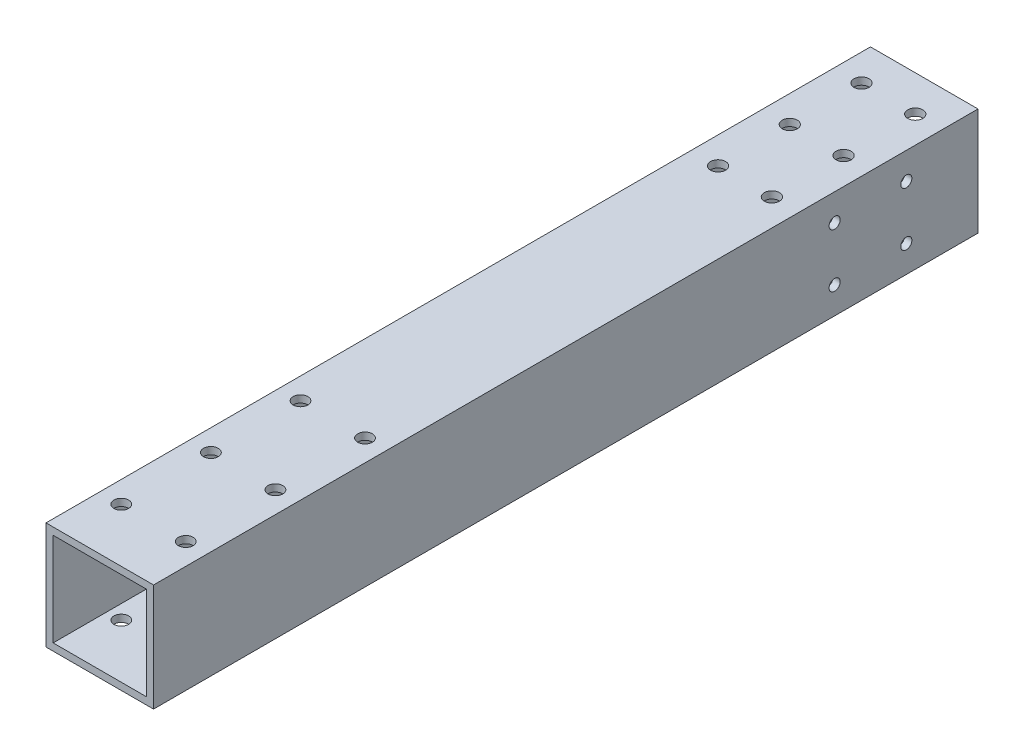
SolidWorks part; units mm, degrees
material "6063-T1"
ref_plane "前视基准面" through (0, 0, 0) normal (0, 0, 1) x (1, 0, 0)
ref_plane "上视基准面" through (0, 0, 0) normal (0, 1, 0) x (1, 0, 0)
ref_plane "右视基准面" through (0, 0, 0) normal (1, 0, 0) x (0, 0, -1)
other "Configuration Table"
sketch "草图1" plane through (0, 0, 0) normal (0, 0, 1) x (1, 0, 0)
  line L1 (-15, 15) -> (15, 15)
  line L2 (-15, 15) -> (-15, -15)
  line L3 (-15, -15) -> (15, -15)
  line L4 (15, 15) -> (15, -15)
  line L5 (-15, 15) -> (15, -15) construction
  line L6 (-15, -15) -> (15, 15) construction
  line L7 (-13, 13) -> (13, 13)
  line L8 (-13, 13) -> (-13, -13)
  line L9 (-13, -13) -> (13, -13)
  line L10 (13, 13) -> (13, -13)
  line L11 (-13, 13) -> (13, -13) construction
  line L12 (-13, -13) -> (13, 13) construction
  point P0 (0, 0)
  point P6 (0, 0)
  dimension "D1" = 30
  dimension "D2" = 2
extrude "凸台-拉伸1" add sketch "草图1" along normal blind 230
sketch "草图2" plane through (0, -15, 0) normal (0, -1, 0) x (1, 0, 0)
  line L0 (-15, 0) -> (15, 0) construction
  line L1 (0, 0) -> (0, 12.9561) construction
  line L2 (0, 230) -> (0, 248.9247) construction
  line L3 (-15, 230) -> (15, 230) construction
  line L4 (-15, 230) -> (-15, 0) construction
  line L5 (15, 230) -> (15, 0) construction
  circle A1 centre (-7.5, 10) radius 2.1
  circle A2 centre (7.5, 10) radius 2.1
  circle A3 centre (7.5, 30) radius 2.1
  circle A4 centre (7.5, 50) radius 2.1
  circle A5 centre (-7.5, 30) radius 2.1
  circle A6 centre (-7.5, 50) radius 2.1
  circle A7 centre (-9, 215) radius 2.05
  circle A8 centre (9, 215) radius 2.05
  circle A9 centre (9, 190) radius 2.05
  circle A10 centre (9, 165) radius 2.05
  circle A11 centre (-9, 190) radius 2.05
  circle A12 centre (-9, 165) radius 2.05
  dimension "D2" = 4.2
  dimension "D6" = 4.1
  dimension "D12" = 6
  dimension "D13" = 7.5
  dimension "D1" = 10
  dimension "D3" = 15
  dimension "D7" = 18
  dimension "D8" = 15
  dimension "D11" = 25
  dimension "D14" = 20
  dimension "D4" = 2
  dimension "D5" = 3
  dimension "D10" = 2
  dimension "D9" = 3
extrude "切除-拉伸1" cut sketch "草图2" against normal through all
sketch "草图4" plane through (15, 0, 0) normal (1, 0, 0) x (0, 0, -1)
  line L0 (0, -15) -> (0, 15) construction
  line L1 (0, 0) -> (-14.5159, 0) construction
  circle A0 centre (-20, 7.5) radius 1.55
  circle A2 centre (-40, 7.5) radius 1.55
  circle A3 centre (-40, -7.5) radius 1.55
  circle A4 centre (-20, -7.5) radius 1.55
  dimension "D1" = 3.1
  dimension "D2" = 20
  dimension "D5" = 15
  dimension "D6" = 20
  dimension "D3" = 2
  dimension "D4" = 2
extrude "切除-拉伸2" cut sketch "草图4" against normal through all
